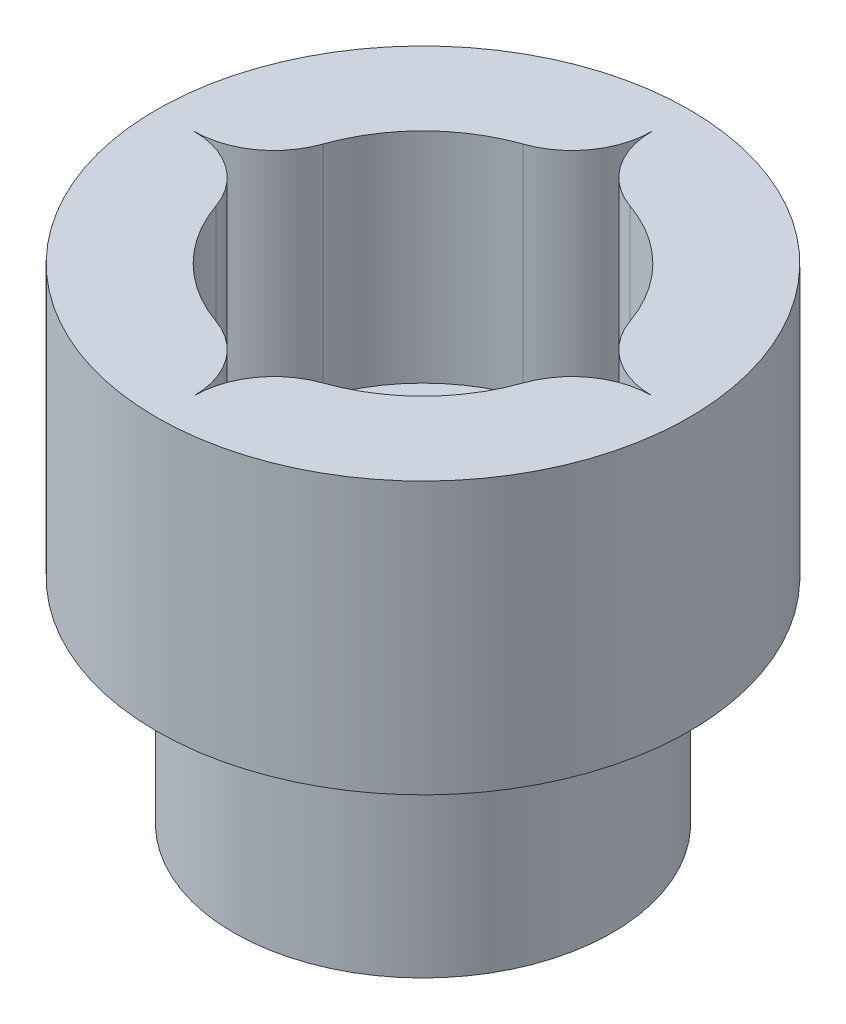
SolidWorks part; units mm, degrees
ref_plane "Front Plane" through (0, 0, 0) normal (0, 0, 1) x (1, 0, 0)
ref_plane "Top Plane" through (0, 0, 0) normal (0, 1, 0) x (1, 0, 0)
ref_plane "Right Plane" through (0, 0, 0) normal (1, 0, 0) x (0, 0, -1)
sketch "Sketch1" plane through (0, 0, 0) normal (0, 1, 0) x (1, 0, 0)
  line L0 (0, 0) -> (0, 1.585) construction
  arc A1 (-1.4289, -0.825) -> (-0.825, -1.4289) centre (0, 0) ccw
  arc A3 (0, 2.8201) -> (0.8084, 1.4384) centre (1.585, 2.8201) ccw
  arc A4 (0, 2.8201) -> (-0.8084, 1.4384) centre (-1.585, 2.8201) cw
  arc A5 (0.0325, -2.8016) -> (-0.825, -1.4289) centre (-1.5521, -2.8373) ccw
  arc A6 (0.0325, -2.8016) -> (0.825, -1.4289) centre (1.6175, -2.8016) cw
  arc A7 (1.4289, 0.825) -> (2.8016, 0.0325) centre (2.8016, 1.6175) ccw
  arc A8 (1.4289, -0.825) -> (2.8016, 0.0325) centre (2.8373, -1.5521) cw
  arc A9 (-1.4289, 0.825) -> (-2.8016, 0.0325) centre (-2.8016, 1.6175) cw
  arc A10 (-1.4289, -0.825) -> (-2.8016, 0.0325) centre (-2.8373, -1.5521) ccw
  arc A12 (1.4072, -0.8615) -> (1.4817, -0.726) centre (0, 0) ccw
  arc A13 (3.1695, -0.0578) -> (3.17, 0) centre (0, 0) ccw
  arc A16 (1.4289, 0.825) -> (0.8084, 1.4384) centre (0, 0) ccw
  arc A17 (1.5868, 0.4522) -> (0.8084, 1.4384) centre (0, 0) ccw
  circle A18 centre (0, 0) radius 3.5511
  arc A19 (-0.8084, 1.4384) -> (-1.4289, 0.825) centre (0, 0) ccw
  arc A20 (1.4072, -0.8615) -> (0.825, -1.4289) centre (0, 0) cw
  dimension "D2" = 3.3
extrude "Boss-Extrude1" add sketch "Sketch1" along normal blind 4
sketch "Sketch2" plane through (0, 4, 0) normal (0, 1, 0) x (1, 0, 0)
  circle A0 centre (0, 0) radius 5
  dimension "D1" = 10
extrude "Boss-Extrude2" add sketch "Sketch2" along normal blind 1
sketch "Sketch3" plane through (0, 5, 0) normal (0, 1, 0) x (1, 0, 0)
  line L0 (0, 0) -> (0, 4.3586) construction
  line L1 (0, 0) -> (3.7279, 0) construction
  line L2 (0, 5) -> (0, 5.2335) construction
  arc A2 (-1.0038, 2.8801) -> (-2.8801, 1.0038) centre (0, 0) ccw
  circle A10 centre (0, 0) radius 5
  arc A14 (-2.8801, -1.0038) -> (-1.0038, -2.8801) centre (0, 0) ccw
  arc A16 (0, 4.293) -> (1.0038, 2.8801) centre (1.4962, 4.293) ccw
  arc A17 (0, 4.293) -> (-1.0038, 2.8801) centre (-1.4962, 4.293) cw
  arc A18 (4.293, 0) -> (2.8801, 1.0038) centre (4.293, 1.4962) cw
  arc A19 (4.293, 0) -> (2.8801, -1.0038) centre (4.293, -1.4962) ccw
  arc A20 (0, -4.293) -> (1.0038, -2.8801) centre (1.4962, -4.293) cw
  arc A21 (0, -4.293) -> (-1.0038, -2.8801) centre (-1.4962, -4.293) ccw
  arc A22 (-4.293, 0) -> (-2.8801, -1.0038) centre (-4.293, -1.4962) cw
  arc A23 (-4.293, 0) -> (-2.8801, 1.0038) centre (-4.293, 1.4962) ccw
  arc A24 (2.8801, 1.0038) -> (1.0038, 2.8801) centre (0, 0) ccw
  arc A25 (1.0038, -2.8801) -> (2.8801, -1.0038) centre (0, 0) ccw
  point P27 (0, 0)
  dimension "D1" = 6.1
  dimension "D2" = 4
  dimension "D3" = 10
extrude "Boss-Extrude3" add sketch "Sketch3" along normal blind 4.1
